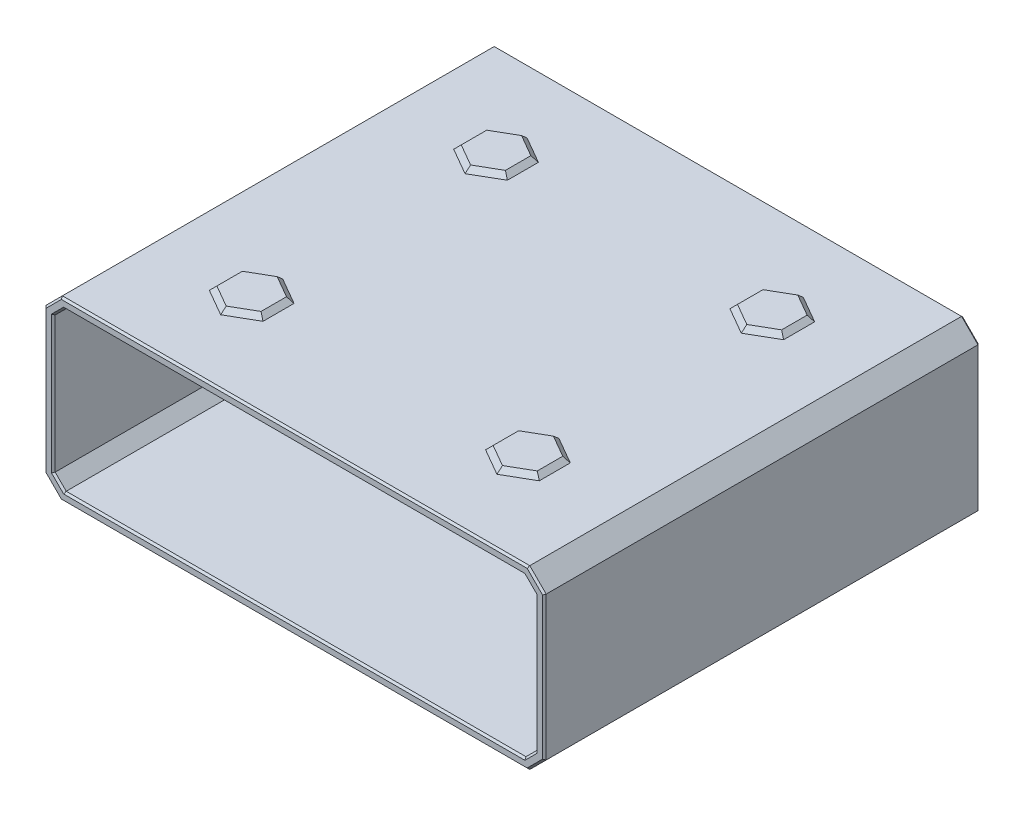
SolidWorks part; units mm, degrees
ref_plane "Front" through (0, 0, 0) normal (0, 0, 1) x (1, 0, 0)
ref_plane "Top" through (0, 0, 0) normal (0, 1, 0) x (1, 0, 0)
ref_plane "Right" through (0, 0, 0) normal (1, 0, 0) x (0, 0, -1)
sketch "Sketch1" plane through (0, 0, 0) normal (0, 0, 1) x (1, 0, 0)
  line L0 (-65.5, -18.5) -> (-62.5, -21.5)
  line L1 (-62.5, -21.5) -> (62.5, -21.5)
  line L2 (-65.5, -18.5) -> (-65.5, 18.5)
  line L3 (-62.5, 21.5) -> (62.5, 21.5)
  line L4 (65.5, -18.5) -> (65.5, 18.5)
  line L5 (-65.5, -21.5) -> (65.5, 21.5) construction
  line L6 (-65.5, 21.5) -> (65.5, -21.5) construction
  line L7 (62.5, -21.5) -> (65.5, -18.5)
  line L8 (62.5, 21.5) -> (65.5, 18.5)
  line L9 (-65.5, 18.5) -> (-62.5, 21.5)
  point P0 (0, 0)
  dimension "D1" = 2
  dimension "D2" = 2
extrude "Walls" add sketch "Sketch1" along normal offset from surface (116.4 mm away) 10 thin
sketch "Sketch2" plane through (0, 0, 0) normal (0, 0, 1) x (1, 0, 0)
  line L12 (68, -19.5355) -> (68, 19.5355)
  line L13 (63.5355, 24) -> (-63.5355, 24)
  line L14 (-68, 19.5355) -> (-68, -19.5355)
  line L15 (-63.5355, -24) -> (63.5355, -24)
  line L16 (68, -19.5355) -> (68, 19.5355)
  line L17 (63.5355, 24) -> (-63.5355, 24)
  line L18 (-68, 19.5355) -> (-68, -19.5355)
  line L19 (-63.5355, -24) -> (63.5355, -24)
  line L24 (63.5355, -24) -> (68, -19.5355)
  line L25 (63.5355, -24) -> (68, -19.5355)
  line L26 (68, 19.5355) -> (63.5355, 24)
  line L27 (68, 19.5355) -> (63.5355, 24)
  line L28 (-63.5355, 24) -> (-68, 19.5355)
  line L29 (-63.5355, 24) -> (-68, 19.5355)
  line L30 (-68, -19.5355) -> (-63.5355, -24)
  line L31 (-68, -19.5355) -> (-63.5355, -24)
  dimension "D1" = 0
extrude "Back Plate" add sketch "Sketch2" against normal blind 2
chamfer "Deburs" distance 0.5 angle 45 32 edges at (0, -24, 116.4) (-65.7678, -21.7678, 116.4) (-68, 0, 116.4) (-65.7678, 21.7678, 116.4) (0, 24, 116.4) (65.7678, 21.7678, 116.4) (68, 0, 116.4) (65.7678, -21.7678, 116.4) (64, -20, 116.4) (65.5, 0, 116.4) (64, 20, 116.4) (0, 21.5, 116.4) (-64, 20, 116.4) (-65.5, 0, 116.4) (-64, -20, 116.4) (0, -21.5, 116.4) (68, 0, -2) (65.7678, 21.7678, -2) (0, 24, -2) (-65.7678, 21.7678, -2) (-68, 0, -2) (-65.7678, -21.7678, -2) (0, -24, -2) (65.7678, -21.7678, -2) (-65.5, 0, 0) (-64, 20, 0) (0, 21.5, 0) (64, 20, 0) (65.5, 0, 0) (64, -20, 0) (0, -21.5, 0) (-64, -20, 0)
sketch "Sketch3" plane through (0, -24, 0) normal (0, 1, 0) x (1, 0, 0)
  line L0 (0, 2) -> (0, -57.2) construction
  line L1 (-37.5548, -23.9808) -> (37.5548, -23.9808) construction
  line L2 (-37.5548, -23.9808) -> (-37.5548, -90.4192) construction
  line L3 (-37.5548, -90.4192) -> (37.5548, -90.4192) construction
  line L4 (37.5548, -23.9808) -> (37.5548, -90.4192) construction
  line L5 (-37.5548, -23.9808) -> (37.5548, -90.4192) construction
  line L6 (-37.5548, -90.4192) -> (37.5548, -23.9808) construction
  line L7 (63.5355, 2) -> (-63.5355, 2) construction
  line L8 (0, -57.2) -> (0, -116.4) construction
  line L9 (-63.5355, -116.4) -> (63.5355, -116.4) construction
  line L10 (-63.5355, -23.9808) -> (-37.5548, -23.9808) construction
  line L11 (-63.5355, -115.9) -> (-63.5355, 1.5) construction
  line L12 (-37.5548, -23.9808) -> (-37.5548, 2) construction
  line L13 (-18.7774, -23.9808) -> (-18.7774, -15.3205) construction
  line L14 (-37.5548, -32.641) -> (-30.0548, -28.3109)
  line L15 (-30.0548, -28.3109) -> (-30.0548, -19.6506)
  line L16 (-30.0548, -19.6506) -> (-37.5548, -15.3205)
  line L17 (-37.5548, -15.3205) -> (-45.0548, -19.6506)
  line L18 (-45.0548, -19.6506) -> (-45.0548, -28.3109)
  line L19 (-45.0548, -28.3109) -> (-37.5548, -32.641)
  line L20 (-18.7774, -15.3205) -> (-18.7774, -6.6603) construction
  line L21 (0, -57.2) -> (37.5548, -57.2) construction
  line L22 (45.0548, -28.3109) -> (37.5548, -32.641)
  line L23 (45.0548, -19.6506) -> (45.0548, -28.3109)
  line L24 (37.5548, -15.3205) -> (45.0548, -19.6506)
  line L25 (30.0548, -19.6506) -> (37.5548, -15.3205)
  line L26 (30.0548, -28.3109) -> (30.0548, -19.6506)
  line L27 (37.5548, -32.641) -> (30.0548, -28.3109)
  line L28 (45.0548, -94.7494) -> (45.0548, -86.0891)
  line L29 (37.5548, -99.0795) -> (45.0548, -94.7494)
  line L30 (30.0548, -94.7494) -> (37.5548, -99.0795)
  line L31 (30.0548, -86.0891) -> (30.0548, -94.7494)
  line L32 (37.5548, -81.759) -> (30.0548, -86.0891)
  line L33 (45.0548, -86.0891) -> (37.5548, -81.759)
  line L34 (-45.0548, -86.0891) -> (-37.5548, -81.759)
  line L35 (-45.0548, -94.7494) -> (-45.0548, -86.0891)
  line L36 (-37.5548, -99.0795) -> (-45.0548, -94.7494)
  line L37 (-30.0548, -94.7494) -> (-37.5548, -99.0795)
  line L38 (-30.0548, -86.0891) -> (-30.0548, -94.7494)
  line L39 (-37.5548, -81.759) -> (-30.0548, -86.0891)
  line L40 (-18.7774, -6.6603) -> (-18.7774, 2) construction
  line L41 (-37.5548, -10.9904) -> (-18.7774, -10.9904) construction
  line L42 (-18.7774, -10.9904) -> (0, -10.9904) construction
  circle A0 centre (-37.5548, -23.9808) radius 7.5 construction
  point P0 (0, -57.2)
  dimension "D1" = 15
extrude "Foot Pocket" [suppressed] cut sketch "Sketch3" along normal blind 1.5 draft 45
sketch "Sketch4" plane through (0, 24, 0) normal (0, -1, 0) x (1, 0, 0)
  line L20 (-30.2548, 94.6339) -> (-37.5548, 98.8486)
  line L21 (-37.5548, 98.8486) -> (-44.8548, 94.6339)
  line L22 (-44.8548, 94.6339) -> (-44.8548, 86.2046)
  line L23 (-44.8548, 86.2046) -> (-37.5548, 81.9899)
  line L24 (-37.5548, 81.9899) -> (-30.2548, 86.2046)
  line L25 (-30.2548, 86.2046) -> (-30.2548, 94.6339)
  line L26 (-30.2548, 94.6339) -> (-37.5548, 98.8486)
  line L27 (-37.5548, 98.8486) -> (-44.8548, 94.6339)
  line L28 (-44.8548, 94.6339) -> (-44.8548, 86.2046)
  line L29 (-44.8548, 86.2046) -> (-37.5548, 81.9899)
  line L30 (-37.5548, 81.9899) -> (-30.2548, 86.2046)
  line L31 (-30.2548, 86.2046) -> (-30.2548, 94.6339)
  line L38 (-37.5548, 32.4101) -> (-44.8548, 28.1954)
  line L39 (-44.8548, 28.1954) -> (-44.8548, 19.7661)
  line L40 (-44.8548, 19.7661) -> (-37.5548, 15.5514)
  line L41 (-37.5548, 15.5514) -> (-30.2548, 19.7661)
  line L42 (-30.2548, 19.7661) -> (-30.2548, 28.1954)
  line L43 (-30.2548, 28.1954) -> (-37.5548, 32.4101)
  line L44 (-37.5548, 32.4101) -> (-44.8548, 28.1954)
  line L45 (-44.8548, 28.1954) -> (-44.8548, 19.7661)
  line L46 (-44.8548, 19.7661) -> (-37.5548, 15.5514)
  line L47 (-37.5548, 15.5514) -> (-30.2548, 19.7661)
  line L48 (-30.2548, 19.7661) -> (-30.2548, 28.1954)
  line L49 (-30.2548, 28.1954) -> (-37.5548, 32.4101)
  line L56 (37.5548, 98.8486) -> (30.2548, 94.6339)
  line L57 (30.2548, 94.6339) -> (30.2548, 86.2046)
  line L58 (30.2548, 86.2046) -> (37.5548, 81.9899)
  line L59 (37.5548, 81.9899) -> (44.8548, 86.2046)
  line L60 (44.8548, 86.2046) -> (44.8548, 94.6339)
  line L61 (44.8548, 94.6339) -> (37.5548, 98.8486)
  line L62 (37.5548, 98.8486) -> (30.2548, 94.6339)
  line L63 (30.2548, 94.6339) -> (30.2548, 86.2046)
  line L64 (30.2548, 86.2046) -> (37.5548, 81.9899)
  line L65 (37.5548, 81.9899) -> (44.8548, 86.2046)
  line L66 (44.8548, 86.2046) -> (44.8548, 94.6339)
  line L67 (44.8548, 94.6339) -> (37.5548, 98.8486)
  line L74 (44.8548, 19.7661) -> (44.8548, 28.1954)
  line L75 (37.5548, 15.5514) -> (44.8548, 19.7661)
  line L76 (30.2548, 19.7661) -> (37.5548, 15.5514)
  line L77 (30.2548, 28.1954) -> (30.2548, 19.7661)
  line L78 (37.5548, 32.4101) -> (30.2548, 28.1954)
  line L79 (44.8548, 28.1954) -> (37.5548, 32.4101)
  line L80 (44.8548, 19.7661) -> (44.8548, 28.1954)
  line L81 (37.5548, 15.5514) -> (44.8548, 19.7661)
  line L82 (30.2548, 19.7661) -> (37.5548, 15.5514)
  line L83 (30.2548, 28.1954) -> (30.2548, 19.7661)
  line L84 (37.5548, 32.4101) -> (30.2548, 28.1954)
  line L85 (44.8548, 28.1954) -> (37.5548, 32.4101)
  dimension "D1" = 0.2
  dimension "D2" = 0.2
  dimension "D3" = 0.2
  dimension "D4" = 0.2
extrude "Feet" add sketch "Sketch4" against normal blind 1.3 draft 45
